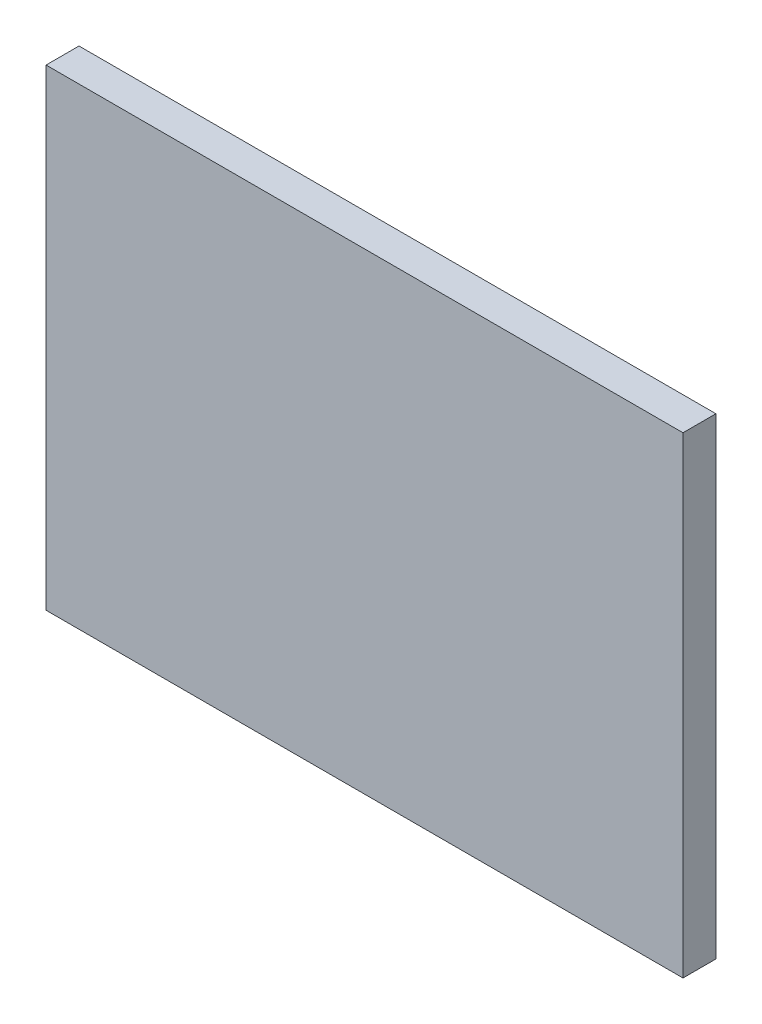
SolidWorks part; units mm, degrees
ref_plane "Front Plane" through (0, 0, 0) normal (0, 0, 1) x (1, 0, 0)
ref_plane "Top Plane" through (0, 0, 0) normal (0, 1, 0) x (1, 0, 0)
ref_plane "Right Plane" through (0, 0, 0) normal (1, 0, 0) x (0, 0, -1)
sketch "Sketch1" plane through (0, 0, 0) normal (0, 0, 1) x (1, 0, 0)
  line L0 (-47.971, 22.5517) -> (10.029, 22.5517)
  line L1 (10.029, 22.5517) -> (10.029, -20.4483)
  line L2 (10.029, -20.4483) -> (-47.971, -20.4483)
  line L3 (-47.971, -20.4483) -> (-47.971, 22.5517)
  point P4 (-47.9655, 24.3434)
  point P5 (26.6747, 17.3657)
  point P6 (26.6747, -12.178)
  point P7 (-47.9655, -18.2649)
  point P8 (26.6747, -13.6626)
  point P9 (20.6229, 17.9925)
  point P10 (20.6229, -14.2919)
  point P11 (20.6229, 19.4711)
  point P12 (-47.9655, 30.438)
  point P13 (20.6229, 22.5517)
  point P14 (-47.9655, -21.562)
  point P15 (20.6229, -15.5241)
  point P16 (-47.971, 30.4497)
  point P17 (-47.971, 22.5517)
  point P18 (12.0345, 22.5517)
  point P19 (-47.971, -15.5241)
  point P20 (12.0345, 22.5517)
  dimension "D1" = 43
  dimension "D2" = 58
extrude "Boss-Extrude1" add sketch "Sketch1" along normal blind 3 contours L2 L3 L0 L1
